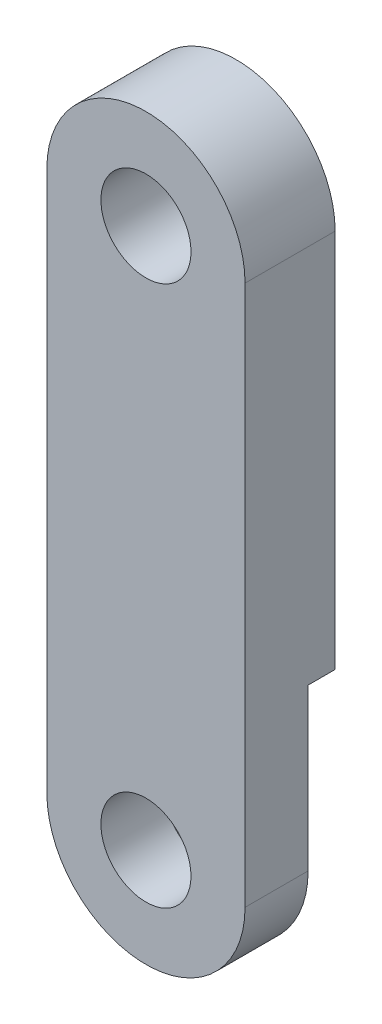
SolidWorks part; units mm, degrees
ref_plane "Front Plane" through (0, 0, 0) normal (1, 0, 0) x (0, 1, 0)
ref_plane "Top Plane" through (0, 0, 0) normal (0, 0, 1) x (0, 1, 0)
ref_plane "Right Plane" through (0, 0, 0) normal (0, 1, 0) x (-1, 0, 0)
sketch "Sketch1" plane through (0, 0, 0) normal (0, 0, 1) x (0, 1, 0)
  line L0 (0, 0) -> (60, 0) construction
  line L1 (0, 11) -> (60, 11)
  line L2 (0, -11) -> (60, -11)
  circle A0 centre (0, 0) radius 5
  circle A1 centre (60, 0) radius 5
  arc A2 (0, 11) -> (0, -11) centre (0, 0) ccw
  arc A3 (60, -11) -> (60, 11) centre (60, 0) ccw
  point P7 (30, 0)
  dimension "D1" = 10
  dimension "D2" = 6
  dimension "D3" = 60
extrude "Boss-Extrude1" add sketch "Sketch1" along normal blind 10
sketch "Sketch2" plane through (0, 0, 0) normal (0, 0, -1) x (1, 0, 0)
  line L0 (9, -17.8606) -> (11, -17.8606)
  line L1 (11, 0) -> (11, -60) construction
  line L2 (-9, -17.8606) -> (-11, -17.8606)
  line L3 (-11, -60) -> (-11, 0) construction
  line L4 (-11, -17.8606) -> (-11, 0)
  line L5 (11, 0) -> (11, -17.8606)
  arc A0 (-9, -17.8606) -> (9, -17.8606) centre (0, 0) ccw
  arc A2 (-11, 0) -> (11, 0) centre (0, 0) cw
  arc A3 (11, 0) -> (-11, 0) centre (0, 0) ccw construction
  dimension "D1" = 40
  dimension "D2" = 2
extrude "Cut-Extrude1" cut sketch "Sketch2" against normal blind 3
equation "\"KneeLinkage\"=60"
equation "\"D3@Sketch1\"=\"KneeLinkage\""
